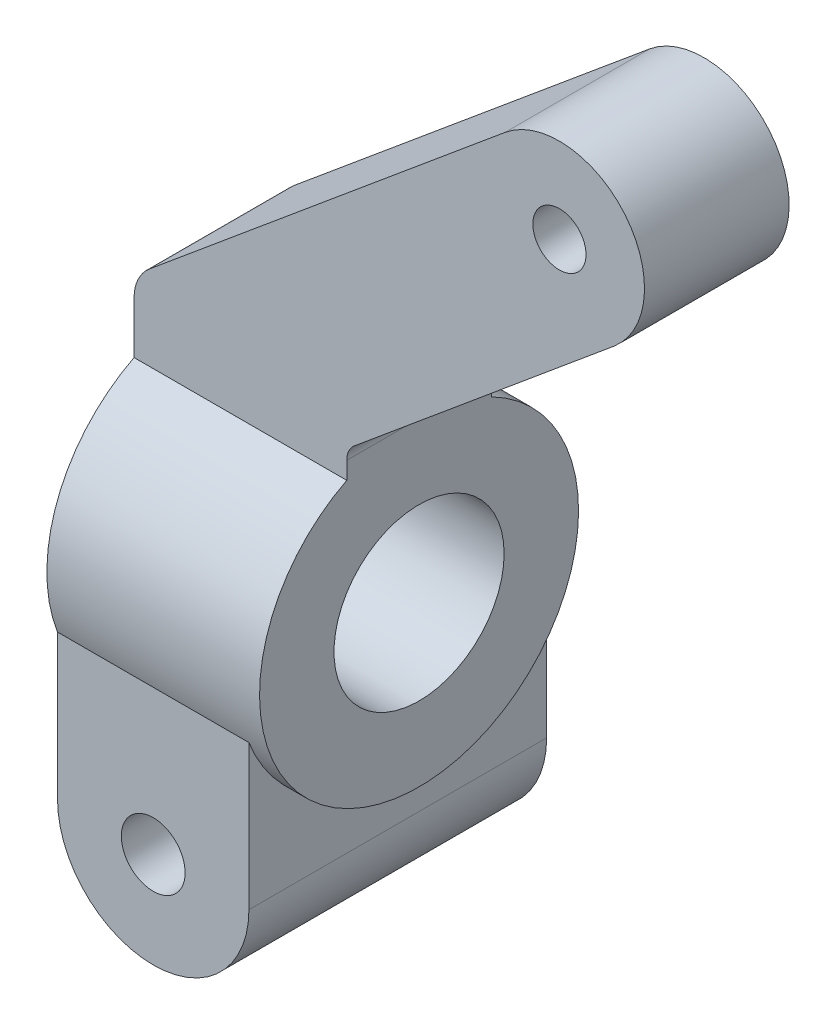
SolidWorks part; units mm, degrees
ref_plane "Front Plane" through (0, 0, 0) normal (0, 0, 1) x (1, 0, 0)
ref_plane "Top Plane" through (0, 0, 0) normal (0, 1, 0) x (1, 0, 0)
ref_plane "Right Plane" through (0, 0, 0) normal (1, 0, 0) x (0, 0, -1)
sketch "Sketch1" plane through (0, 0, 0) normal (1, 0, 0) x (0, 0, -1)
  circle A0 centre (0, 0) radius 7.5
  dimension "D1" = 15
extrude "Boss-Extrude1" add sketch "Sketch1" along normal blind 10
sketch "Sketch2" plane through (0, 0, 0) normal (0, 0, 1) x (1, 0, 0)
  line L0 (0, 0) -> (0, 9.1151)
  line L1 (0.7203, 10.6521) -> (17.4405, 24.5739)
  line L2 (22.5595, 18.4261) -> (10.3601, 8.2685)
  line L3 (10, 7.5) -> (10, 0)
  line L4 (0, 0) -> (10, 0)
  line L5 (10, -7.5) -> (10, 7.5) construction
  line L6 (10, 7.5) -> (0, 7.5) construction
  arc A0 (22.5595, 18.4261) -> (17.4405, 24.5739) centre (20, 21.5) ccw
  arc A1 (0, 9.1151) -> (0.7203, 10.6521) centre (2, 9.1151) cw
  arc A2 (10.3601, 8.2685) -> (10, 7.5) centre (11, 7.5) ccw
  point P11 (19.3988, 22.4643)
  point P15 (22.5868, 18.449)
  point P16 (10, 7.7849)
  point P20 (0, 0)
  point P22 (0, 0)
  dimension "D1" = 2
  dimension "D2" = 1
  dimension "D3" = 8
  dimension "D4" = 10
  dimension "D5" = 14
extrude "Boss-Extrude2" add sketch "Sketch2" along normal mid plane 6.8
sketch "Sketch3" plane through (0, 0, 0) normal (0, 0, 1) x (1, 0, 0)
  line L0 (4.5, 0) -> (4.5, -9.5) construction
  line L1 (9, 0) -> (9, -9.5)
  line L2 (0, 0) -> (0, -9.5)
  line L3 (0, 6.6851) -> (0, -7.5) construction
  line L4 (0, -7.5) -> (10, -7.5) construction
  line L5 (0, 0) -> (9, 0)
  arc A0 (9, 0) -> (0, 0) centre (4.5, 0) ccw
  arc A1 (0, -9.5) -> (9, -9.5) centre (4.5, -9.5) ccw
  point P2 (4.5, -4.75)
  dimension "D1" = 9
  dimension "D2" = 2
extrude "Boss-Extrude3" add sketch "Sketch3" along normal mid plane 14
sketch "Sketch4" plane through (0, 0, 7) normal (0, 0, 1) x (1, 0, 0)
  circle A0 centre (4.5, -9.5) radius 1.5
  arc A1 (0, -9.5) -> (9, -9.5) centre (4.5, -9.5) ccw construction
  dimension "D1" = 3
extrude "Cut-Extrude1" cut sketch "Sketch4" against normal through all both and the other way through all
sketch "Sketch5" plane through (10, 0, 0) normal (1, 0, 0) x (0, 0, -1)
  circle A0 centre (0, 0) radius 4
  dimension "D1" = 8
extrude "Cut-Extrude2" cut sketch "Sketch5" against normal through all
sketch "Sketch6" plane through (0, 0, 3.4) normal (0, 0, 1) x (1, 0, 0)
  circle A0 centre (20, 21.5) radius 1.25
  dimension "D1" = 2.5
extrude "Cut-Extrude3" cut sketch "Sketch6" against normal through all both and the other way through all
